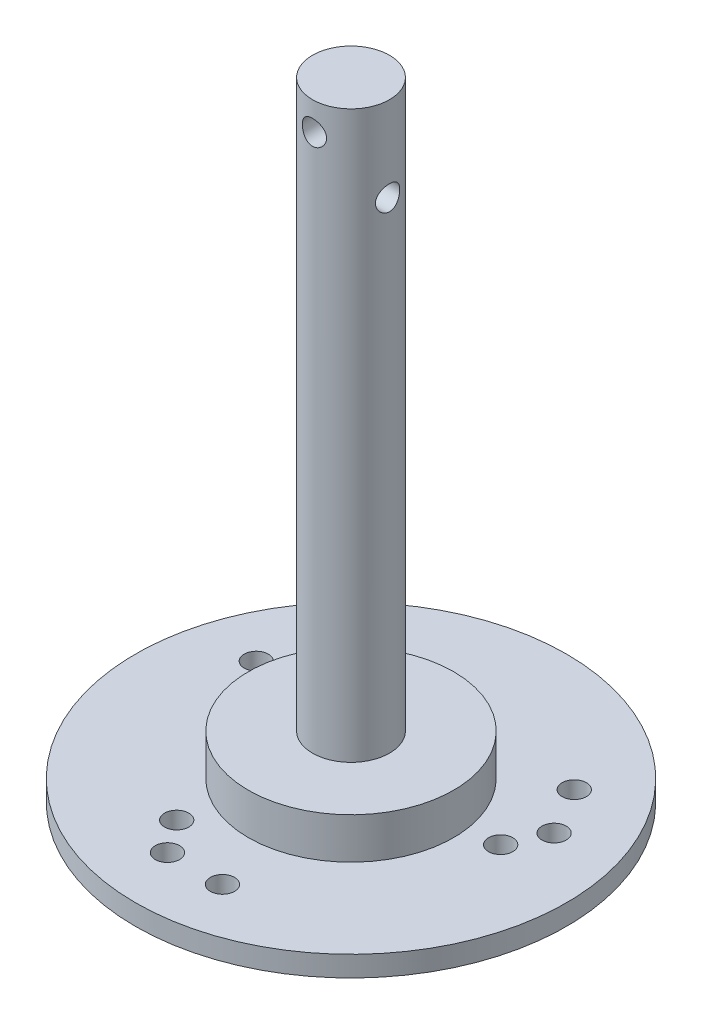
SolidWorks part; units mm, degrees
ref_plane "Front Plane" through (0, 0, 0) normal (0, 0, 1) x (1, 0, 0)
ref_plane "Top Plane" through (0, 0, 0) normal (0, 1, 0) x (1, 0, 0)
ref_plane "Right Plane" through (0, 0, 0) normal (1, 0, 0) x (0, 0, -1)
sketch "Sketch1" plane through (0, 0, 0) normal (0, 1, 0) x (1, 0, 0)
  circle A0 centre (0, 0) radius 26.65
extrude "Boss-Extrude1" add sketch "Sketch1" along normal blind 2.54
sketch "Sketch2" plane through (0, 2.54, 0) normal (0, 1, 0) x (1, 0, 0)
  circle A0 centre (0, 0) radius 12.7
  dimension "D1" = 25.4
extrude "Boss-Extrude2" add sketch "Sketch2" along normal blind 5.08
sketch "Sketch4" plane through (0, 7.62, 0) normal (0, 1, 0) x (1, 0, 0)
  circle A0 centre (0, 0) radius 4.7625
extrude "Boss-Extrude3" add sketch "Sketch4" along normal blind 70
sketch "Sketch6" plane through (0, 0, 0) normal (0, -1, 0) x (-1, 0, 0)
  circle A0 centre (6.3138, -15.2429) radius 1.5
  circle A1 centre (-16.3576, 2.1535) radius 1.5
  circle A2 centre (10.0438, 13.0894) radius 1.5
  circle A5 centre (-3.4035, -19.3022) radius 1.5
  circle A10 centre (-18.418, 6.7036) radius 1.5
  circle A11 centre (-15.0145, 12.5986) radius 1.5
  circle A16 centre (15.0145, 12.5986) radius 1.5
  circle A17 centre (18.418, 6.7036) radius 1.5
  circle A22 centre (3.4035, -19.3022) radius 1.5
  circle A23 centre (9.8, -16.9741) radius 1.5 [skipped]
  circle A24 centre (15.0145, -12.5986) radius 1.5 [skipped]
  circle A25 centre (18.418, -6.7036) radius 1.5 [skipped]
  circle A26 centre (-9.8, -16.9741) radius 1.5 [skipped]
  circle A27 centre (-15.0145, -12.5986) radius 1.5 [skipped]
  circle A28 centre (-18.418, -6.7036) radius 1.5 [skipped]
  circle A29 centre (-19.6, 0) radius 1.5 [skipped]
  circle A30 centre (9.8, 16.9741) radius 1.5 [skipped]
  circle A31 centre (3.4035, 19.3022) radius 1.5 [skipped]
  circle A32 centre (-3.4035, 19.3022) radius 1.5 [skipped]
  circle A33 centre (-9.8, 16.9741) radius 1.5 [skipped]
  circle A34 centre (19.6, 0) radius 1.5 [skipped]
  point P15 (0, 0)
  point P20 (0, 0)
  point P53 (0, 0)
  dimension "D1" = 3
  dimension "D3" = 18
extrude "Cut-Extrude2" cut sketch "Sketch6" against normal through all
sketch "Sketch7" plane through (0, 0, 0) normal (0, 0, 1) x (1, 0, 0)
  line L0 (4.7625, 77.62) -> (-4.7625, 77.62) construction
  circle A1 centre (0, 74.12) radius 1.5
  dimension "D2" = 3.5
extrude "Cut-Extrude3" cut sketch "Sketch7" along normal through all and the other way through all
sketch "Sketch8" plane through (0, 0, 0) normal (1, 0, 0) x (0, 0, -1)
  line L0 (4.7625, 77.62) -> (-4.7625, 77.62) construction
  circle A0 centre (0, 67.12) radius 1.5
  dimension "D1" = 10.5
extrude "Cut-Extrude4" cut sketch "Sketch8" against normal through all and the other way through all
